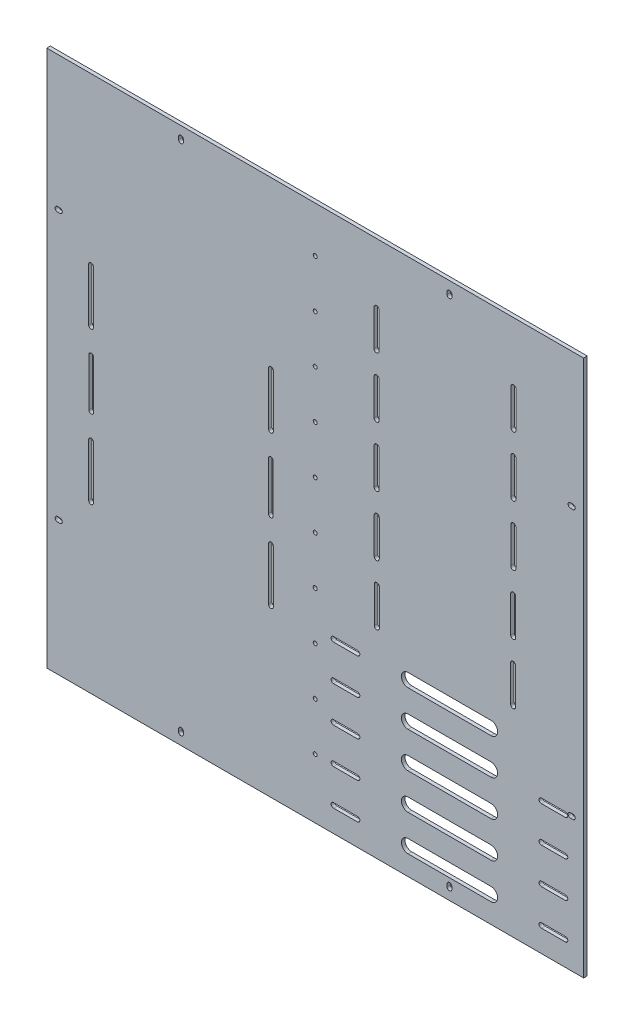
SolidWorks part; units mm, degrees
ref_plane "Piano frontale" through (0, 0, 0) normal (0, 0, 1) x (1, 0, 0)
ref_plane "Piano superiore" through (0, 0, 0) normal (0, 1, 0) x (1, 0, 0)
ref_plane "Piano destro" through (0, 0, 0) normal (1, 0, 0) x (0, 0, -1)
sketch "Schizzo1" plane through (0, 0, 0) normal (0, 0, 1) x (1, 0, 0)
  line L0 (10, 448) -> (10, -28.2593) construction
  line L1 (0, 0) -> (448, 0)
  line L2 (0, 0) -> (0, 448)
  line L3 (0, 448) -> (448, 448)
  line L4 (448, 0) -> (448, 448)
  line L5 (0, 224) -> (448, 224) construction
  line L6 (224, 448) -> (224, 0) construction
  line L7 (438, 448) -> (438, -28.2593) construction
  line L8 (0, 438) -> (525.0128, 438) construction
  line L9 (0, 10) -> (525.0128, 10) construction
  line L10 (0, 448) -> (0, 224) construction
  line L11 (0, 448) -> (0, 224) construction
  line L12 (9, 336) -> (11, 336) construction
  line L13 (9, 338) -> (11, 338)
  line L14 (9, 334) -> (11, 334)
  line L15 (0, 336) -> (224, 336) construction
  line L16 (9, 112) -> (11, 112) construction
  line L17 (9, 110) -> (11, 110)
  line L18 (9, 114) -> (11, 114)
  line L19 (439, 112) -> (437, 112) construction
  line L20 (439, 110) -> (437, 110)
  line L21 (439, 114) -> (437, 114)
  line L22 (439, 336) -> (437, 336) construction
  line L23 (439, 338) -> (437, 338)
  line L24 (439, 334) -> (437, 334)
  line L25 (112, 448) -> (112, 224) construction
  line L26 (112, 439) -> (112, 437) construction
  line L27 (114, 439) -> (114, 437)
  line L28 (110, 439) -> (110, 437)
  line L29 (336, 439) -> (336, 437) construction
  line L30 (334, 439) -> (334, 437)
  line L31 (338, 439) -> (338, 437)
  line L32 (112, 9) -> (112, 11) construction
  line L33 (114, 9) -> (114, 11)
  line L34 (110, 9) -> (110, 11)
  line L35 (336, 9) -> (336, 11) construction
  line L36 (334, 9) -> (334, 11)
  line L37 (338, 9) -> (338, 11)
  line L38 (36.9588, 287.1268) -> (36.9588, 448) construction
  line L39 (36.9588, 265.3661) -> (36.9588, 309.3661) construction
  line L40 (34.9588, 265.3661) -> (34.9588, 309.3661)
  line L41 (38.9588, 265.3661) -> (38.9588, 309.3661)
  line L42 (36.9588, 182.6339) -> (36.9588, 138.6339) construction
  line L43 (34.9588, 182.6339) -> (34.9588, 138.6339)
  line L44 (38.9588, 182.6339) -> (38.9588, 138.6339)
  line L45 (37.087, 204.1388) -> (37.087, 244.1388) construction
  line L46 (35.087, 204.1388) -> (35.087, 244.1388)
  line L47 (39.087, 204.1388) -> (39.087, 244.1388)
  line L48 (187.0412, 265.3661) -> (187.0412, 309.3661) construction
  line L49 (189.0412, 265.3661) -> (189.0412, 309.3661)
  line L50 (185.0412, 265.3661) -> (185.0412, 309.3661)
  line L51 (186.913, 204.1388) -> (186.913, 244.1388) construction
  line L52 (188.913, 204.1388) -> (188.913, 244.1388)
  line L53 (184.913, 204.1388) -> (184.913, 244.1388)
  line L54 (187.0412, 182.6339) -> (187.0412, 138.6339) construction
  line L55 (189.0412, 182.6339) -> (189.0412, 138.6339)
  line L56 (185.0412, 182.6339) -> (185.0412, 138.6339)
  line L57 (239.2518, 140.4111) -> (259.2518, 140.4111) construction
  line L58 (239.2518, 142.4111) -> (259.2518, 142.4111)
  line L59 (239.2518, 138.4111) -> (259.2518, 138.4111)
  line L60 (239.2518, 110.4111) -> (259.2518, 110.4111) construction
  line L61 (239.2518, 112.4111) -> (259.2518, 112.4111)
  line L62 (239.2518, 108.4111) -> (259.2518, 108.4111)
  line L63 (224, 224) -> (448, 0) construction
  line L64 (448, 224) -> (224, 0) construction
  line L65 (224, 224) -> (448, 224) construction
  line L66 (336, 112) -> (335.9892, 224) construction
  line L67 (336, 112) -> (448, 112) construction
  line L68 (239.2518, 80.4111) -> (259.2518, 80.4111) construction
  line L69 (239.2518, 82.4111) -> (259.2518, 82.4111)
  line L70 (239.2518, 78.4111) -> (259.2518, 78.4111)
  line L71 (239.2518, 50.4111) -> (259.2518, 50.4111) construction
  line L72 (239.2518, 52.4111) -> (259.2518, 52.4111)
  line L73 (239.2518, 48.4111) -> (259.2518, 48.4111)
  line L74 (370.6967, 112) -> (301.4749, 112) construction
  line L75 (370.6967, 106.4796) -> (301.4749, 106.4796)
  line L76 (370.6967, 117.5204) -> (301.4749, 117.5204)
  line L77 (370.6967, 142) -> (301.4749, 142) construction
  line L78 (370.6967, 136.4796) -> (301.4749, 136.4796)
  line L79 (370.6967, 147.5204) -> (301.4749, 147.5204)
  line L80 (370.6967, 82) -> (301.4749, 82) construction
  line L81 (370.6967, 76.4796) -> (301.4749, 76.4796)
  line L82 (370.6967, 87.5204) -> (301.4749, 87.5204)
  line L83 (275.4109, 167.4043) -> (275.4109, 197.4043) construction
  line L84 (273.3109, 167.4043) -> (273.3109, 197.4043)
  line L85 (277.5109, 167.4043) -> (277.5109, 197.4043)
  line L86 (275.3436, 217.4042) -> (275.3436, 247.4042) construction
  line L87 (273.2436, 217.4042) -> (273.2436, 247.4042)
  line L88 (277.4436, 217.4042) -> (277.4436, 247.4042)
  line L89 (275.2763, 267.4042) -> (275.2763, 297.4042) construction
  line L90 (273.1763, 267.4042) -> (273.1763, 297.4042)
  line L91 (277.3763, 267.4042) -> (277.3763, 297.4042)
  line L92 (275.209, 317.4041) -> (275.209, 347.4041) construction
  line L93 (273.109, 317.4041) -> (273.109, 347.4041)
  line L94 (277.309, 317.4041) -> (277.309, 347.4041)
  line L95 (275.1417, 367.4041) -> (275.1417, 397.4041) construction
  line L96 (273.0417, 367.4041) -> (273.0417, 397.4041)
  line L97 (277.2417, 367.4041) -> (277.2417, 397.4041)
  line L98 (332.2796, 390.6311) -> (332.2796, 165.3043) construction
  line L99 (389.1483, 167.4043) -> (389.1483, 197.4043) construction
  line L100 (391.2483, 167.4043) -> (391.2483, 197.4043)
  line L101 (387.0483, 167.4043) -> (387.0483, 197.4043)
  line L102 (389.2156, 217.4042) -> (389.2156, 247.4042) construction
  line L103 (391.3156, 217.4042) -> (391.3156, 247.4042)
  line L104 (387.1156, 217.4042) -> (387.1156, 247.4042)
  line L105 (389.2829, 267.4042) -> (389.2829, 297.4042) construction
  line L106 (391.3829, 267.4042) -> (391.3829, 297.4042)
  line L107 (387.1829, 267.4042) -> (387.1829, 297.4042)
  line L108 (389.3502, 317.4041) -> (389.3502, 347.4041) construction
  line L109 (391.4502, 317.4041) -> (391.4502, 347.4041)
  line L110 (387.2502, 317.4041) -> (387.2502, 347.4041)
  line L111 (389.4175, 367.4041) -> (389.4175, 397.4041) construction
  line L112 (391.5175, 367.4041) -> (391.5175, 397.4041)
  line L113 (387.3175, 367.4041) -> (387.3175, 397.4041)
  line L114 (336, 112) -> (202.345, 112) construction
  line L115 (239.2518, 20.4111) -> (259.2518, 20.4111) construction
  line L116 (239.2518, 22.4111) -> (259.2518, 22.4111)
  line L117 (239.2518, 18.4111) -> (259.2518, 18.4111)
  line L118 (422.7427, 140.4278) -> (422.7537, 83.6056) construction
  line L119 (432.7658, 20.4298) -> (412.7658, 20.4259) construction
  line L120 (432.7655, 22.4298) -> (412.7655, 22.4259)
  line L121 (432.7662, 18.4298) -> (412.7662, 18.4259)
  line L122 (249.2518, 140.4111) -> (249.2518, 83.5889) construction
  line L123 (432.7601, 50.4298) -> (412.7601, 50.4259) construction
  line L124 (432.7597, 52.4298) -> (412.7597, 52.4259)
  line L125 (432.7605, 48.4298) -> (412.7605, 48.4259)
  line L126 (432.7543, 80.4298) -> (412.7543, 80.4259) construction
  line L127 (432.7539, 82.4298) -> (412.7539, 82.4259)
  line L128 (432.7547, 78.4298) -> (412.7547, 78.4259)
  line L129 (432.7485, 110.4298) -> (412.7485, 110.4259) construction
  line L130 (432.7481, 112.4298) -> (412.7481, 112.4259)
  line L131 (432.7489, 108.4298) -> (412.7489, 108.4259)
  line L132 (432.7427, 140.4298) -> (412.7427, 140.4259) construction
  line L133 (370.6967, 52) -> (301.4749, 52) construction
  line L134 (370.6967, 46.4796) -> (301.4749, 46.4796)
  line L135 (370.6967, 57.5204) -> (301.4749, 57.5204)
  line L136 (370.6967, 22) -> (301.4749, 22) construction
  line L137 (370.6967, 16.4796) -> (301.4749, 16.4796)
  line L138 (370.6967, 27.5204) -> (301.4749, 27.5204)
  arc A0 (9, 338) -> (9, 334) centre (9, 336) ccw
  arc A1 (11, 334) -> (11, 338) centre (11, 336) ccw
  arc A2 (9, 110) -> (9, 114) centre (9, 112) cw
  arc A3 (11, 114) -> (11, 110) centre (11, 112) cw
  arc A4 (439, 110) -> (439, 114) centre (439, 112) ccw
  arc A5 (437, 114) -> (437, 110) centre (437, 112) ccw
  arc A6 (439, 338) -> (439, 334) centre (439, 336) cw
  arc A7 (437, 334) -> (437, 338) centre (437, 336) cw
  arc A8 (114, 439) -> (110, 439) centre (112, 439) ccw
  arc A9 (110, 437) -> (114, 437) centre (112, 437) ccw
  arc A10 (334, 439) -> (338, 439) centre (336, 439) cw
  arc A11 (338, 437) -> (334, 437) centre (336, 437) cw
  arc A12 (114, 9) -> (110, 9) centre (112, 9) cw
  arc A13 (110, 11) -> (114, 11) centre (112, 11) cw
  arc A14 (334, 9) -> (338, 9) centre (336, 9) ccw
  arc A15 (338, 11) -> (334, 11) centre (336, 11) ccw
  arc A16 (34.9588, 265.3661) -> (38.9588, 265.3661) centre (36.9588, 265.3661) ccw
  arc A17 (38.9588, 309.3661) -> (34.9588, 309.3661) centre (36.9588, 309.3661) ccw
  arc A18 (34.9588, 182.6339) -> (38.9588, 182.6339) centre (36.9588, 182.6339) cw
  arc A19 (38.9588, 138.6339) -> (34.9588, 138.6339) centre (36.9588, 138.6339) cw
  arc A20 (35.087, 204.1388) -> (39.087, 204.1388) centre (37.087, 204.1388) ccw
  arc A21 (39.087, 244.1388) -> (35.087, 244.1388) centre (37.087, 244.1388) ccw
  arc A22 (189.0412, 265.3661) -> (185.0412, 265.3661) centre (187.0412, 265.3661) cw
  arc A23 (185.0412, 309.3661) -> (189.0412, 309.3661) centre (187.0412, 309.3661) cw
  arc A24 (188.913, 204.1388) -> (184.913, 204.1388) centre (186.913, 204.1388) cw
  arc A25 (184.913, 244.1388) -> (188.913, 244.1388) centre (186.913, 244.1388) cw
  arc A26 (189.0412, 182.6339) -> (185.0412, 182.6339) centre (187.0412, 182.6339) ccw
  arc A27 (185.0412, 138.6339) -> (189.0412, 138.6339) centre (187.0412, 138.6339) ccw
  arc A28 (239.2518, 142.4111) -> (239.2518, 138.4111) centre (239.2518, 140.4111) ccw
  arc A29 (259.2518, 138.4111) -> (259.2518, 142.4111) centre (259.2518, 140.4111) ccw
  arc A30 (239.2518, 112.4111) -> (239.2518, 108.4111) centre (239.2518, 110.4111) ccw
  arc A31 (259.2518, 108.4111) -> (259.2518, 112.4111) centre (259.2518, 110.4111) ccw
  arc A32 (239.2518, 82.4111) -> (239.2518, 78.4111) centre (239.2518, 80.4111) ccw
  arc A33 (259.2518, 78.4111) -> (259.2518, 82.4111) centre (259.2518, 80.4111) ccw
  arc A34 (239.2518, 52.4111) -> (239.2518, 48.4111) centre (239.2518, 50.4111) ccw
  arc A35 (259.2518, 48.4111) -> (259.2518, 52.4111) centre (259.2518, 50.4111) ccw
  circle A36 centre (224, 49.7735) radius 1.65
  circle A37 centre (224, 89.7735) radius 1.65
  circle A38 centre (224, 129.7735) radius 1.65
  circle A39 centre (224, 169.7735) radius 1.65
  circle A40 centre (224, 209.7735) radius 1.65
  circle A41 centre (224, 249.7735) radius 1.65
  circle A42 centre (224, 289.7735) radius 1.65
  circle A43 centre (224, 329.7735) radius 1.65
  circle A44 centre (224, 369.7735) radius 1.65
  circle A45 centre (224, 409.7735) radius 1.65
  arc A46 (370.6967, 106.4796) -> (370.6967, 117.5204) centre (370.6967, 112) ccw
  arc A47 (301.4749, 117.5204) -> (301.4749, 106.4796) centre (301.4749, 112) ccw
  arc A48 (370.6967, 136.4796) -> (370.6967, 147.5204) centre (370.6967, 142) ccw
  arc A49 (301.4749, 147.5204) -> (301.4749, 136.4796) centre (301.4749, 142) ccw
  arc A50 (370.6967, 76.4796) -> (370.6967, 87.5204) centre (370.6967, 82) ccw
  arc A51 (301.4749, 87.5204) -> (301.4749, 76.4796) centre (301.4749, 82) ccw
  arc A52 (273.3109, 167.4043) -> (277.5109, 167.4043) centre (275.4109, 167.4043) ccw
  arc A53 (277.5109, 197.4043) -> (273.3109, 197.4043) centre (275.4109, 197.4043) ccw
  arc A54 (273.2436, 217.4042) -> (277.4436, 217.4042) centre (275.3436, 217.4042) ccw
  arc A55 (277.4436, 247.4042) -> (273.2436, 247.4042) centre (275.3436, 247.4042) ccw
  arc A56 (273.1763, 267.4042) -> (277.3763, 267.4042) centre (275.2763, 267.4042) ccw
  arc A57 (277.3763, 297.4042) -> (273.1763, 297.4042) centre (275.2763, 297.4042) ccw
  arc A58 (273.109, 317.4041) -> (277.309, 317.4041) centre (275.209, 317.4041) ccw
  arc A59 (277.309, 347.4041) -> (273.109, 347.4041) centre (275.209, 347.4041) ccw
  arc A60 (273.0417, 367.4041) -> (277.2417, 367.4041) centre (275.1417, 367.4041) ccw
  arc A61 (277.2417, 397.4041) -> (273.0417, 397.4041) centre (275.1417, 397.4041) ccw
  arc A62 (391.2483, 167.4043) -> (387.0483, 167.4043) centre (389.1483, 167.4043) cw
  arc A63 (387.0483, 197.4043) -> (391.2483, 197.4043) centre (389.1483, 197.4043) cw
  arc A64 (391.3156, 217.4042) -> (387.1156, 217.4042) centre (389.2156, 217.4042) cw
  arc A65 (387.1156, 247.4042) -> (391.3156, 247.4042) centre (389.2156, 247.4042) cw
  arc A66 (391.3829, 267.4042) -> (387.1829, 267.4042) centre (389.2829, 267.4042) cw
  arc A67 (387.1829, 297.4042) -> (391.3829, 297.4042) centre (389.2829, 297.4042) cw
  arc A68 (391.4502, 317.4041) -> (387.2502, 317.4041) centre (389.3502, 317.4041) cw
  arc A69 (387.2502, 347.4041) -> (391.4502, 347.4041) centre (389.3502, 347.4041) cw
  arc A70 (391.5175, 367.4041) -> (387.3175, 367.4041) centre (389.4175, 367.4041) cw
  arc A71 (387.3175, 397.4041) -> (391.5175, 397.4041) centre (389.4175, 397.4041) cw
  arc A72 (239.2518, 22.4111) -> (239.2518, 18.4111) centre (239.2518, 20.4111) ccw
  arc A73 (259.2518, 18.4111) -> (259.2518, 22.4111) centre (259.2518, 20.4111) ccw
  arc A74 (432.7655, 22.4298) -> (432.7662, 18.4298) centre (432.7658, 20.4298) cw
  arc A75 (412.7662, 18.4259) -> (412.7655, 22.4259) centre (412.7658, 20.4259) cw
  arc A76 (432.7597, 52.4298) -> (432.7605, 48.4298) centre (432.7601, 50.4298) cw
  arc A77 (412.7605, 48.4259) -> (412.7597, 52.4259) centre (412.7601, 50.4259) cw
  arc A78 (432.7539, 82.4298) -> (432.7547, 78.4298) centre (432.7543, 80.4298) cw
  arc A79 (412.7547, 78.4259) -> (412.7539, 82.4259) centre (412.7543, 80.4259) cw
  arc A80 (432.7481, 112.4298) -> (432.7489, 108.4298) centre (432.7485, 110.4298) cw
  arc A81 (412.7489, 108.4259) -> (412.7481, 112.4259) centre (412.7485, 110.4259) cw
  arc A82 (370.6967, 46.4796) -> (370.6967, 57.5204) centre (370.6967, 52) ccw
  arc A83 (301.4749, 57.5204) -> (301.4749, 46.4796) centre (301.4749, 52) ccw
  arc A84 (370.6967, 16.4796) -> (370.6967, 27.5204) centre (370.6967, 22) ccw
  arc A85 (301.4749, 27.5204) -> (301.4749, 16.4796) centre (301.4749, 22) ccw
  point P19 (10, 336)
  point P28 (10, 112)
  point P35 (438, 112)
  point P42 (438, 336)
  point P49 (112, 438)
  point P52 (112, 438)
  point P59 (336, 438)
  point P66 (112, 10)
  point P73 (336, 10)
  point P82 (36.9588, 287.3661)
  point P89 (36.9588, 160.6339)
  point P96 (37.087, 224.1388)
  point P103 (187.0412, 287.3661)
  point P110 (186.913, 224.1388)
  point P117 (187.0412, 160.6339)
  point P124 (249.2518, 140.4111)
  point P132 (249.2518, 110.4111)
  point P143 (249.2518, 80.4111)
  point P150 (249.2518, 50.4111)
  point P178 (336.0858, 112)
  point P183 (336.0858, 142)
  point P192 (336.0858, 82)
  point P197 (275.4109, 182.4043)
  point P206 (275.3436, 232.4042)
  point P213 (275.2763, 282.4042)
  point P220 (275.209, 332.4041)
  point P227 (275.1417, 382.4041)
  point P234 (389.1483, 182.4043)
  point P241 (389.2156, 232.4042)
  point P248 (389.2829, 282.4042)
  point P255 (389.3502, 332.4041)
  point P262 (389.4175, 382.4041)
  point P271 (249.2518, 20.4111)
  point P279 (422.7658, 20.4278)
  point P288 (422.7601, 50.4278)
  point P295 (422.7543, 80.4278)
  point P302 (422.7485, 110.4278)
  point P313 (336.0858, 52)
  point P320 (336.0858, 22)
  dimension "D5" = 1
  dimension "D14" = 3.3
  dimension "D23" = 5
  dimension "D1" = 448
  dimension "D2" = 448
  dimension "D3" = 10
  dimension "D4" = 10
  dimension "D6" = 4
  dimension "D7" = 112
  dimension "D8" = 112
  dimension "D9" = 1
  dimension "D10" = 4
  dimension "D11" = 4
  dimension "D12" = 22
  dimension "D13" = 4
  dimension "D15" = 10
  dimension "D16" = 20
  dimension "D17" = 5
  dimension "D18" = 30
  dimension "D20" = 4.2
  dimension "D21" = 30
  dimension "D22" = 5
extrude "Estrusione-Estrusione1" add sketch "Schizzo1" against normal blind 3
